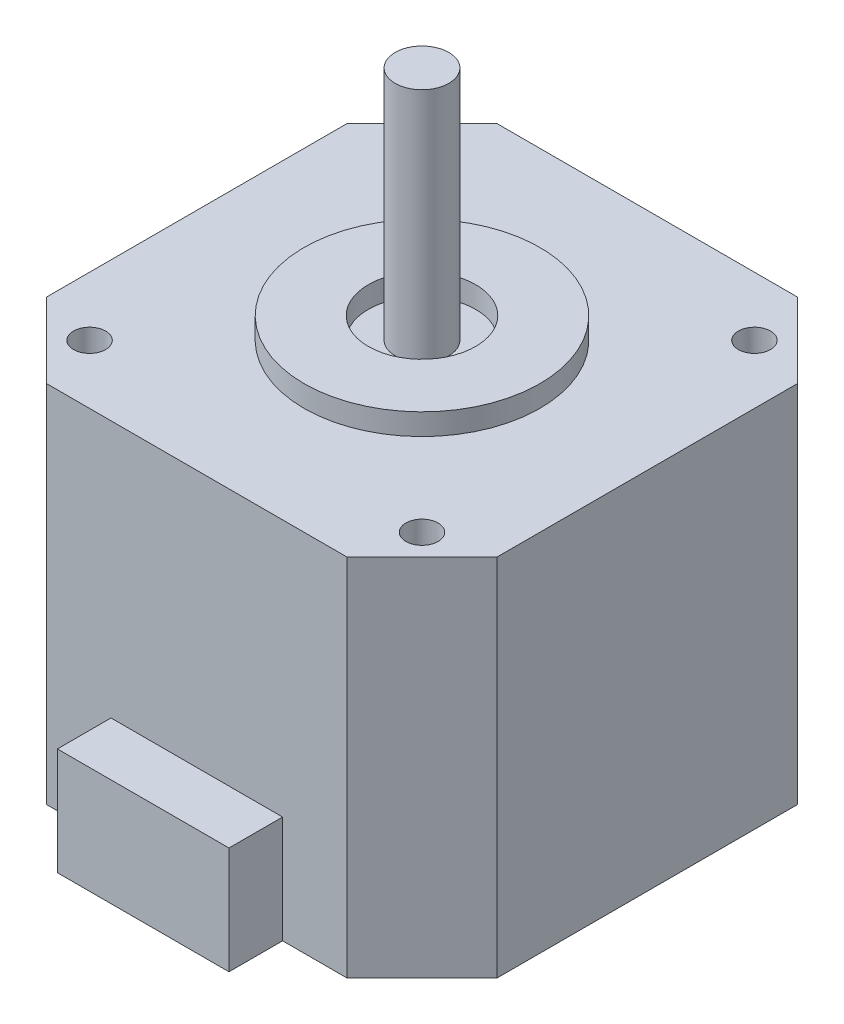
SolidWorks part; units mm, degrees
ref_plane "Front Plane" through (0, 0, 0) normal (0, 0, 1) x (1, 0, 0)
ref_plane "Top Plane" through (0, 0, 0) normal (0, 1, 0) x (1, 0, 0)
ref_plane "Right Plane" through (0, 0, 0) normal (1, 0, 0) x (0, 0, -1)
sketch "Sketch1" plane through (0, 0, 0) normal (0, 1, 0) x (1, 0, 0)
  line L0 (0, 35) -> (7, 42)
  line L1 (0, 0) -> (42, 0)
  line L2 (0, 0) -> (0, 42)
  line L3 (0, 42) -> (42, 42)
  line L4 (42, 0) -> (42, 42)
  line L5 (0, 7) -> (7, 0)
  line L6 (35, 42) -> (42, 35)
  line L7 (42, 7) -> (35, 0)
  dimension "D1" = 42
  dimension "D2" = 42
  dimension "D3" = 28
  dimension "D4" = 28
  dimension "D5" = 28
  dimension "D6" = 28
  dimension "D7" = 7
  dimension "D8" = 7
  dimension "D9" = 7
  dimension "D10" = 7
extrude "Boss-Extrude1" add sketch "Sketch1" along normal blind 34 contours L7 L4 L6 L3 L0 L2 L5 L1
sketch "Sketch2" plane through (0, 0, 0) normal (0, 0, 1) x (1, 0, 0)
  line L0 (7, 0) -> (35, 0) construction
  line L1 (13, 0) -> (29, 0)
  line L2 (13, 0) -> (13, 10)
  line L3 (13, 10) -> (29, 10)
  line L4 (29, 0) -> (29, 10)
  point P6 (21, 0)
  point P7 (21, 10)
  dimension "D1" = 10
  dimension "D2" = 16
extrude "Boss-Extrude2" add sketch "Sketch2" along normal blind 5
sketch "Sketch3" plane through (0, 34, 0) normal (0, 1, 0) x (1, 0, 0)
  line L0 (29, 0) -> (13, 0) construction
  line L1 (42, 7) -> (42, 35) construction
  circle A0 centre (21, 21) radius 11
  circle A1 centre (21, 21) radius 5
  point P6 (21, 0)
  point P9 (42, 21)
  dimension "D1" = 22
  dimension "D2" = 10
extrude "Boss-Extrude3" add sketch "Sketch3" along normal blind 2
sketch "Sketch4" plane through (0, 34, 0) normal (0, 1, 0) x (1, 0, 0)
  circle A0 centre (21, 21) radius 2.5
  dimension "D1" = 5
extrude "Boss-Extrude4" add sketch "Sketch4" along normal blind 22
sketch "Sketch5" plane through (0, 34, 0) normal (0, 1, 0) x (1, 0, 0)
  line L0 (29, 0) -> (13, 0) construction
  line L1 (5.5, 36.5) -> (36.5, 36.5) construction
  line L2 (5.5, 36.5) -> (5.5, 5.5) construction
  line L3 (5.5, 5.5) -> (36.5, 5.5) construction
  line L4 (36.5, 36.5) -> (36.5, 5.5) construction
  line L5 (0, 7) -> (0, 35) construction
  circle A0 centre (5.5, 36.5) radius 1.5
  circle A1 centre (5.5, 5.5) radius 1.5
  circle A2 centre (36.5, 5.5) radius 1.5
  circle A3 centre (36.5, 36.5) radius 1.5
  point P14 (21, 0)
  point P15 (21, 5.5)
  point P18 (0, 21)
  point P19 (5.5, 21)
  dimension "D1" = 3
  dimension "D2" = 31
  dimension "D3" = 31
extrude "Cut-Extrude1" cut sketch "Sketch5" against normal blind 22
